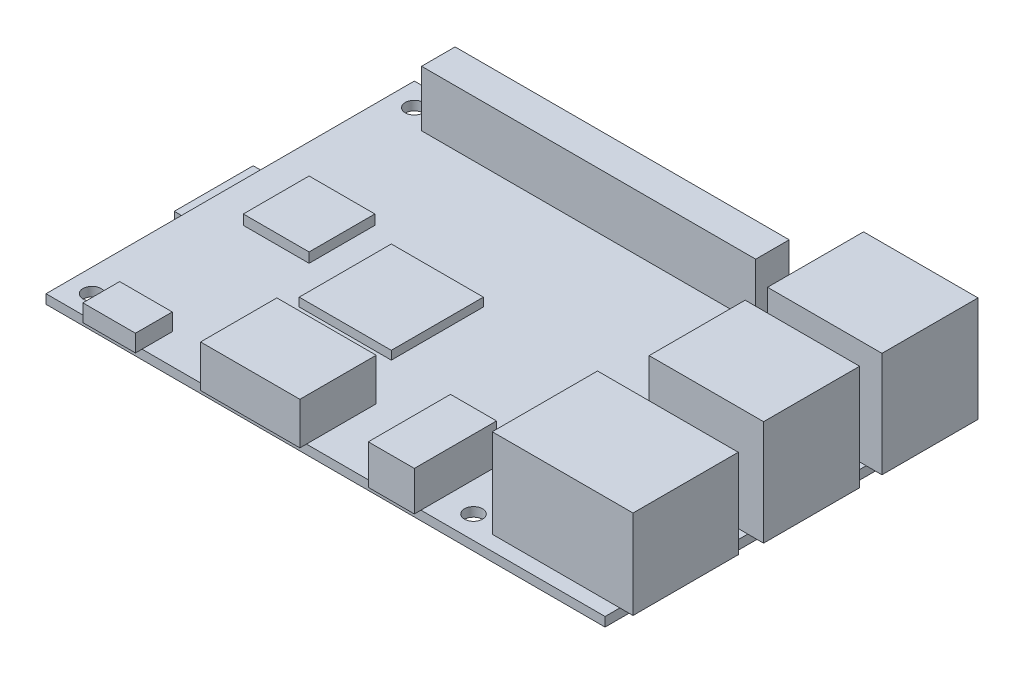
SolidWorks part; units mm, degrees
ref_plane "Front Plane" through (0, 0, 0) normal (0, 0, 1) x (1, 0, 0)
ref_plane "Top Plane" through (0, 0, 0) normal (0, 1, 0) x (1, 0, 0)
ref_plane "Right Plane" through (0, 0, 0) normal (1, 0, 0) x (0, 0, -1)
other "Configuration Table"
sketch "Sketch1" plane through (0, 0, 0) normal (0, 1, 0) x (1, 0, 0)
  line L1 (0, 0) -> (85, 0)
  line L2 (0, 0) -> (0, 56)
  line L3 (0, 56) -> (85, 56)
  line L4 (85, 0) -> (85, 56)
extrude "PCB" add sketch "Sketch1" along normal blind 1.4
sketch "Sketch2" plane through (0, 0, 0) normal (0, 1, 0) x (1, 0, 0)
  circle A0 centre (3.5, 3.5) radius 1.375
extrude "M2_5_hole_1" cut sketch "Sketch2" against normal through all and the other way through all
sketch "Sketch3" plane through (0, 0, 0) normal (0, 1, 0) x (1, 0, 0)
  circle A0 centre (61.5, 3.5) radius 1.375
extrude "M2_5_hole_2" cut sketch "Sketch3" against normal through all and the other way through all
sketch "Sketch4" plane through (0, 0, 0) normal (0, 1, 0) x (1, 0, 0)
  circle A0 centre (3.5, 52.5) radius 1.375
extrude "M2_5_hole_3" cut sketch "Sketch4" against normal through all and the other way through all
sketch "Sketch5" plane through (0, 0, 0) normal (0, 1, 0) x (1, 0, 0)
  circle A0 centre (61.5, 52.5) radius 1.375
extrude "M2_5_hole_4" cut sketch "Sketch5" against normal through all and the other way through all
sketch "Sketch6" plane through (0, 0, 0) normal (0, 1, 0) x (1, 0, 0)
  line L1 (7.1, 50) -> (57.9, 50)
  line L2 (7.1, 50) -> (7.1, 55.1)
  line L3 (7.1, 55.1) -> (57.9, 55.1)
  line L4 (57.9, 50) -> (57.9, 55.1)
extrude "GPIO_header_40pin" add sketch "Sketch6" along normal blind 8.5 from offset 1.4
sketch "Sketch7" plane through (0, 0, 0) normal (0, 1, 0) x (1, 0, 0)
  line L1 (70, 21.7) -> (87.4, 21.7)
  line L2 (70, 21.7) -> (70, 36.3)
  line L3 (70, 36.3) -> (87.4, 36.3)
  line L4 (87.4, 21.7) -> (87.4, 36.3)
extrude "USB_pair_1" add sketch "Sketch7" along normal blind 16 from offset 1.4
sketch "Sketch8" plane through (0, 0, 0) normal (0, 1, 0) x (1, 0, 0)
  line L1 (70, 39.7) -> (87.4, 39.7)
  line L2 (70, 39.7) -> (70, 54.3)
  line L3 (70, 54.3) -> (87.4, 54.3)
  line L4 (87.4, 39.7) -> (87.4, 54.3)
extrude "USB_pair_2" add sketch "Sketch8" along normal blind 16 from offset 1.4
sketch "Sketch9" plane through (0, 0, 0) normal (0, 1, 0) x (1, 0, 0)
  line L1 (65.6, 2.25) -> (87, 2.25)
  line L2 (65.6, 2.25) -> (65.6, 18.25)
  line L3 (65.6, 18.25) -> (87, 18.25)
  line L4 (87, 2.25) -> (87, 18.25)
extrude "Ethernet_RJ45" add sketch "Sketch9" along normal blind 13.5 from offset 1.4
sketch "Sketch10" plane through (0, 0, 0) normal (0, 1, 0) x (1, 0, 0)
  line L1 (21, 17.5) -> (35, 17.5)
  line L2 (21, 17.5) -> (21, 31.5)
  line L3 (21, 31.5) -> (35, 31.5)
  line L4 (35, 17.5) -> (35, 31.5)
extrude "SoC_BCM2837B0" add sketch "Sketch10" along normal blind 1.3 from offset 1.4
sketch "Sketch11" plane through (0, 0, 0) normal (0, 1, 0) x (1, 0, 0)
  line L1 (24.5, -1) -> (39.6, -1)
  line L2 (24.5, -1) -> (24.5, 10.6)
  line L3 (24.5, 10.6) -> (39.6, 10.6)
  line L4 (39.6, -1) -> (39.6, 10.6)
extrude "HDMI" add sketch "Sketch11" along normal blind 6.4 from offset 1.4
sketch "Sketch12" plane through (0, 0, 0) normal (0, 1, 0) x (1, 0, 0)
  line L1 (6.6, -1) -> (14.6, -1)
  line L2 (6.6, -1) -> (6.6, 4.6)
  line L3 (6.6, 4.6) -> (14.6, 4.6)
  line L4 (14.6, -1) -> (14.6, 4.6)
extrude "Micro_USB_power" add sketch "Sketch12" along normal blind 2.6 from offset 1.4
sketch "Sketch13" plane through (0, 0, 0) normal (0, 1, 0) x (1, 0, 0)
  line L1 (50, -1) -> (57, -1)
  line L2 (50, -1) -> (50, 11.5)
  line L3 (50, 11.5) -> (57, 11.5)
  line L4 (57, -1) -> (57, 11.5)
extrude "Audio_jack" add sketch "Sketch13" along normal blind 6 from offset 1.4
sketch "Sketch14" plane through (0, 0, 0) normal (0, 1, 0) x (1, 0, 0)
  line L1 (6, 24) -> (16, 24)
  line L2 (6, 24) -> (6, 34)
  line L3 (6, 34) -> (16, 34)
  line L4 (16, 24) -> (16, 34)
extrude "WiFi_shield" add sketch "Sketch14" along normal blind 1.5 from offset 1.4
sketch "Sketch15" plane through (0, 0, 0) normal (0, 1, 0) x (1, 0, 0)
  line L1 (55, 12) -> (64, 12)
  line L2 (55, 12) -> (55, 21)
  line L3 (55, 21) -> (64, 21)
  line L4 (64, 12) -> (64, 21)
extrude "LAN_chip" add sketch "Sketch15" along normal blind 1 from offset 1.4
sketch "Sketch16" plane through (0, 0, 0) normal (0, 1, 0) x (1, 0, 0)
  line L1 (-2.5, 22) -> (10.5, 22)
  line L2 (-2.5, 22) -> (-2.5, 34)
  line L3 (-2.5, 34) -> (10.5, 34)
  line L4 (10.5, 22) -> (10.5, 34)
extrude "MicroSD_slot" add sketch "Sketch16" against normal blind 1.5
